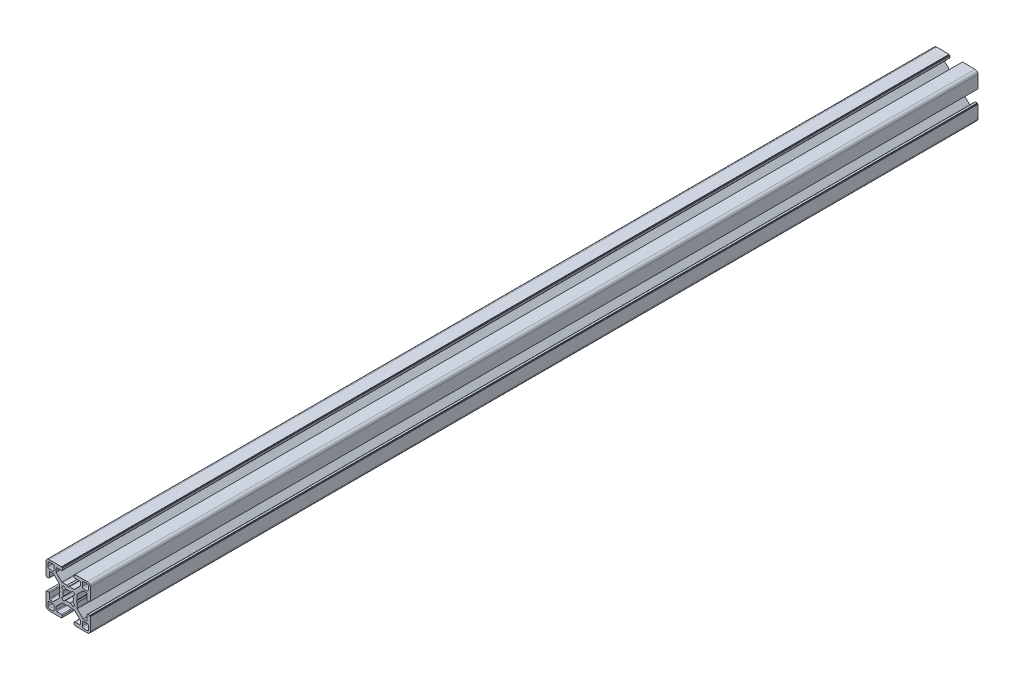
SolidWorks part; units mm, degrees
ref_plane "Front Plane" through (0, 0, 0) normal (0, 0, 1) x (1, 0, 0)
ref_plane "Top Plane" through (0, 0, 0) normal (0, 1, 0) x (1, 0, 0)
ref_plane "Right Plane" through (0, 0, 0) normal (1, 0, 0) x (0, 0, -1)
sketch "Sketch1" plane through (0, 0, 0) normal (0, 0, 1) x (1, 0, 0)
  line L0 (-15, 0) -> (15, 0) construction
  line L1 (0, -15) -> (0, 15) construction
  line L2 (-4.5, 15) -> (4.5, 15) construction
  line L3 (-4, -15) -> (4, -15) construction
  line L4 (-4.5, 15) -> (-4.5, 14.5)
  line L5 (-4.5, 14.5) -> (-4, 14.5)
  line L6 (-4, 14.5) -> (-4, 13.29)
  line L7 (-4.5, 12.79) -> (-7.7675, 12.79)
  line L8 (-8.2675, 12.29) -> (-8.2675, 10.2707)
  line L9 (-8.1211, 9.9171) -> (-4.3504, 6.1464)
  line L10 (-3.9968, 6) -> (0, 6)
  line L11 (0, 0) -> (-15, 15) construction
  line L12 (-4.5, 15) -> (-12.968, 15)
  line L14 (-12.705, 9.5135) -> (-10.5135, 9.5135)
  line L15 (-13.705, 10.5135) -> (-13.705, 12.705)
  line L16 (-12.705, 13.705) -> (-10.5135, 13.705)
  line L17 (-9.5135, 10.5135) -> (-9.5135, 12.705)
  line L18 (-13.705, 9.5135) -> (-9.5135, 13.705) construction
  line L19 (-13.705, 13.705) -> (-9.5135, 9.5135) construction
  line L20 (-3.1568, 4.5038) -> (-1.5303, 3.1477) construction
  line L21 (-4.5038, 3.1568) -> (-3.1477, 1.5303) construction
  line L22 (-6, 3.9968) -> (-6, 0)
  line L23 (-9.9171, 8.1211) -> (-6.1464, 4.3504)
  line L24 (-15, 4.5) -> (-15, 12.968)
  line L25 (-12.29, 8.2675) -> (-10.2707, 8.2675)
  line L26 (-12.79, 4.5) -> (-12.79, 7.7675)
  line L27 (-14.5, 4) -> (-13.29, 4)
  line L28 (-14.5, 4.5) -> (-14.5, 4)
  line L29 (-15, 4.5) -> (-14.5, 4.5)
  circle A0 centre (0, 0) radius 3.5
  arc A1 (-12.968, 15) -> (-15, 12.968) centre (-12.968, 12.968) ccw
  circle A2 centre (0, 0) radius 5.5 construction
  arc A3 (-10.5135, 9.5135) -> (-9.5135, 10.5135) centre (-10.5135, 10.5135) ccw
  arc A4 (-13.705, 12.705) -> (-12.705, 13.705) centre (-12.705, 12.705) cw
  arc A5 (-10.5135, 13.705) -> (-9.5135, 12.705) centre (-10.5135, 12.705) cw
  arc A6 (-12.705, 9.5135) -> (-13.705, 10.5135) centre (-12.705, 10.5135) cw
  arc A7 (-12.79, 4.5) -> (-13.29, 4) centre (-13.29, 4.5) cw
  arc A8 (-12.29, 8.2675) -> (-12.79, 7.7675) centre (-12.29, 7.7675) ccw
  arc A9 (-9.9171, 8.1211) -> (-10.2707, 8.2675) centre (-10.2707, 7.7675) ccw
  arc A10 (-6, 3.9968) -> (-6.1464, 4.3504) centre (-6.5, 3.9968) ccw
  arc A11 (-4.3504, 6.1464) -> (-3.9968, 6) centre (-3.9968, 6.5) ccw
  arc A12 (-4, 13.29) -> (-4.5, 12.79) centre (-4.5, 13.29) cw
  arc A13 (-7.7675, 12.79) -> (-8.2675, 12.29) centre (-7.7675, 12.29) ccw
  arc A14 (-8.2675, 10.2707) -> (-8.1211, 9.9171) centre (-7.7675, 10.2707) ccw
  point P4 (0, 0)
  point P8 (0, 0)
  point P13 (0, 15)
  point P15 (0, -15)
  point P16 (0, 6)
  point P23 (-11.6092, 11.6093)
  point P26 (0, 6)
  point P62 (-12.79, 4)
  point P65 (-12.79, 8.2675)
  point P68 (-10.0636, 8.2675)
  point P71 (-6, 4.2039)
  point P74 (-4.2039, 6)
  point P77 (-4, 12.79)
  point P80 (-8.2675, 12.79)
  point P83 (-8.2675, 10.0636)
  dimension "Center Hole Diameter" = 7
  dimension "D11" = 2.032
  dimension "D9" = 11
  dimension "D13" = 1
  dimension "D14" = 0.5
  dimension "Rail Height" = 30
  dimension "Rail Width" = 30
  dimension "T-Slot Width" = 8
  dimension "T-Slot Depth" = 9
  dimension "D1" = 9
  dimension "D2" = 45
  dimension "D3" = 8
  dimension "D4" = 2.21
  dimension "D5" = 16.535
  dimension "D7" = 2.54
  dimension "D6" = 1.295
  dimension "D8" = 1.246
  dimension "D10" = 10.36
  dimension "D12" = 1.905
sketch "Sketch2" plane through (0, 0, 0) normal (1, 0, 0) x (0, 0, -1)
  line L0 (-76.2, 0) -> (76.2, 0) construction
  line L2 (0, -15) -> (0, 15) construction
  line L3 (0, -15) -> (0, 15) construction
  line L4 (-76.2, -15) -> (-76.2, 15) construction
  line L5 (76.2, -15) -> (76.2, 15) construction
  point P0 (-38.7, 0)
  point P3 (0, 0)
  point P4 (38.7, 0)
  point P12 (-76.2, 0)
  point P14 (76.2, 0)
  dimension "Length" = 152.4
  dimension "D1" = 37.5
sketch "Sketch3" plane through (0, 0, 0) normal (0, 0, 1) x (1, 0, 0)
  line L0 (-4.5038, 3.1568) -> (-3.1477, 1.5303)
  line L1 (0, 3.5) -> (0, 5.5)
  line L2 (-5.5, 0) -> (-3.5, 0)
  line L7 (-6, 3.9968) -> (-6, 0) construction
  line L31 (-9.9171, 8.1211) -> (-6.1464, 4.3504) construction
  line L117 (-12.29, 8.2675) -> (-10.2707, 8.2675) construction
  line L118 (-12.79, 4.5) -> (-12.79, 7.7675) construction
  line L157 (-12.705, 9.5135) -> (-10.5135, 9.5135)
  line L158 (-9.5135, 10.5135) -> (-9.5135, 12.705)
  line L163 (-10.5135, 13.705) -> (-12.705, 13.705)
  line L164 (-13.705, 12.705) -> (-13.705, 10.5135)
  line L165 (-12.705, 9.5135) -> (-10.5135, 9.5135)
  line L166 (-9.5135, 10.5135) -> (-9.5135, 12.705)
  line L167 (-10.5135, 13.705) -> (-12.705, 13.705)
  line L168 (-13.705, 12.705) -> (-13.705, 10.5135)
  line L169 (-14.5, 4) -> (-13.29, 4) construction
  line L170 (-14.5, 4.5) -> (-14.5, 4) construction
  line L171 (-15, 4.5) -> (-14.5, 4.5) construction
  line L172 (-15, 4.5) -> (-15, 12.968) construction
  line L173 (-4.5, 15) -> (-12.968, 15) construction
  line L174 (-4.5, 15) -> (-4.5, 14.5) construction
  line L175 (-4.5, 14.5) -> (-4, 14.5) construction
  line L176 (-4, 14.5) -> (-4, 13.29) construction
  line L177 (-4.5, 12.79) -> (-7.7675, 12.79) construction
  line L178 (-8.2675, 12.29) -> (-8.2675, 10.2707) construction
  line L179 (-8.1211, 9.9171) -> (-4.3504, 6.1464) construction
  line L180 (-3.9968, 6) -> (0, 6) construction
  line L181 (-6, 3.9968) -> (-6, 0.866)
  line L182 (-9.9171, 8.1211) -> (-6.1464, 4.3504)
  line L183 (-12.29, 8.2675) -> (-10.2707, 8.2675)
  line L184 (-12.79, 4.5) -> (-12.79, 7.7675)
  line L185 (-14.5, 4) -> (-13.29, 4)
  line L186 (-14.5, 4.5) -> (-14.5, 4)
  line L187 (-15, 4.5) -> (-14.5, 4.5)
  line L188 (-15, 4.5) -> (-15, 12.968)
  line L189 (-4.5, 15) -> (-12.968, 15)
  line L190 (-4.5, 15) -> (-4.5, 14.5)
  line L191 (-4.5, 14.5) -> (-4, 14.5)
  line L192 (-4, 14.5) -> (-4, 13.29)
  line L193 (-4.5, 12.79) -> (-7.7675, 12.79)
  line L194 (-8.2675, 12.29) -> (-8.2675, 10.2707)
  line L195 (-8.1211, 9.9171) -> (-4.3504, 6.1464)
  line L196 (-3.9968, 6) -> (-0.866, 6)
  line L197 (-0.866, 6) -> (0, 5.5)
  line L198 (0, -15) -> (0, 15) construction
  line L199 (0, 0) -> (-15, 15) construction
  line L200 (0, 0) -> (-15, 15) construction
  line L201 (-3.1568, 4.5038) -> (-1.5303, 3.1477) construction
  line L202 (-3.1568, 4.5038) -> (-1.5303, 3.1477)
  line L203 (-6, 0.866) -> (-5.5, 0)
  line L204 (-15, 0) -> (15, 0) construction
  line L205 (-15, 0) -> (15, 0) construction
  line L206 (0, -15) -> (0, 15) construction
  arc A0 (-3.5, 0) -> (-3.1477, 1.5303) centre (0, 0) cw
  arc A10 (-6, 3.9968) -> (-6.1464, 4.3504) centre (-6.5, 3.9968) ccw construction
  circle A16 centre (0, 0) radius 3.5
  arc A18 (0, 3.5) -> (-1.5303, 3.1477) centre (0, 0) ccw
  arc A20 (-9.9171, 8.1211) -> (-10.2707, 8.2675) centre (-10.2707, 7.7675) ccw construction
  arc A22 (-12.29, 8.2675) -> (-12.79, 7.7675) centre (-12.29, 7.7675) ccw construction
  arc A28 (-13.29, 4) -> (-12.79, 4.5) centre (-13.29, 4.5) ccw construction
  arc A29 (-10.5135, 9.5135) -> (-9.5135, 10.5135) centre (-10.5135, 10.5135) ccw
  arc A30 (-9.5135, 12.705) -> (-10.5135, 13.705) centre (-10.5135, 12.705) ccw
  arc A31 (-12.705, 13.705) -> (-13.705, 12.705) centre (-12.705, 12.705) ccw
  arc A32 (-13.705, 10.5135) -> (-12.705, 9.5135) centre (-12.705, 10.5135) ccw
  arc A33 (-10.5135, 9.5135) -> (-9.5135, 10.5135) centre (-10.5135, 10.5135) ccw
  arc A34 (-9.5135, 12.705) -> (-10.5135, 13.705) centre (-10.5135, 12.705) ccw
  arc A35 (-12.705, 13.705) -> (-13.705, 12.705) centre (-12.705, 12.705) ccw
  arc A36 (-13.705, 10.5135) -> (-12.705, 9.5135) centre (-12.705, 10.5135) ccw
  arc A37 (-12.968, 15) -> (-15, 12.968) centre (-12.968, 12.968) ccw construction
  arc A38 (-4.5, 12.79) -> (-4, 13.29) centre (-4.5, 13.29) ccw construction
  arc A39 (-7.7675, 12.79) -> (-8.2675, 12.29) centre (-7.7675, 12.29) ccw construction
  arc A40 (-8.2675, 10.2707) -> (-8.1211, 9.9171) centre (-7.7675, 10.2707) ccw construction
  arc A41 (-4.3504, 6.1464) -> (-3.9968, 6) centre (-3.9968, 6.5) ccw construction
  arc A42 (-6, 3.9968) -> (-6.1464, 4.3504) centre (-6.5, 3.9968) ccw
  arc A43 (-9.9171, 8.1211) -> (-10.2707, 8.2675) centre (-10.2707, 7.7675) ccw
  arc A44 (-12.29, 8.2675) -> (-12.79, 7.7675) centre (-12.29, 7.7675) ccw
  arc A45 (-13.29, 4) -> (-12.79, 4.5) centre (-13.29, 4.5) ccw
  arc A46 (-12.968, 15) -> (-15, 12.968) centre (-12.968, 12.968) ccw
  arc A47 (-4.5, 12.79) -> (-4, 13.29) centre (-4.5, 13.29) ccw
  arc A48 (-7.7675, 12.79) -> (-8.2675, 12.29) centre (-7.7675, 12.29) ccw
  arc A49 (-8.2675, 10.2707) -> (-8.1211, 9.9171) centre (-7.7675, 10.2707) ccw
  arc A50 (-4.3504, 6.1464) -> (-3.9968, 6) centre (-3.9968, 6.5) ccw
  circle A51 centre (0, 0) radius 5.5 construction
  arc A52 (-3.1568, 4.5038) -> (-4.5038, 3.1568) centre (0, 0) ccw
  dimension "D3" = 60
  dimension "D4" = 60
  dimension "D1" = 0
  dimension "D2" = 0
extrude "Boss-Extrude1" add sketch "Sketch3" along normal mid plane 600
pattern_circular "CirPattern1" count 4 over 360 about axis through (0, 0, 0) along (0, 0, 1) of "Boss-Extrude1"
ref_plane "Contact Plane1" through (15, 0, 0) normal (1, 0, 0) x (0, 0, -1)
ref_plane "Contact Plane2" through (0, -15, 0) normal (0, 1, 0) x (1, 0, 0)
ref_plane "Contact Plane3" through (-15, 0, 0) normal (1, 0, 0) x (0, 0, -1)
ref_plane "Contact Plane4" through (0, 15, 0) normal (0, 1, 0) x (1, 0, 0)
equation "\"D1@Sketch2\" = \"Rail Height@Sketch1\" * 1.25"
equation "\"D1@Sketch1\"=\"T-Slot Width@Sketch1\"+1mm"
equation "\"D3@Sketch1\"=\"T-Slot Width@Sketch1\""
equation "\"D1@Boss-Extrude1\"=\"Length\""
equation "\"Length\"= 600"
